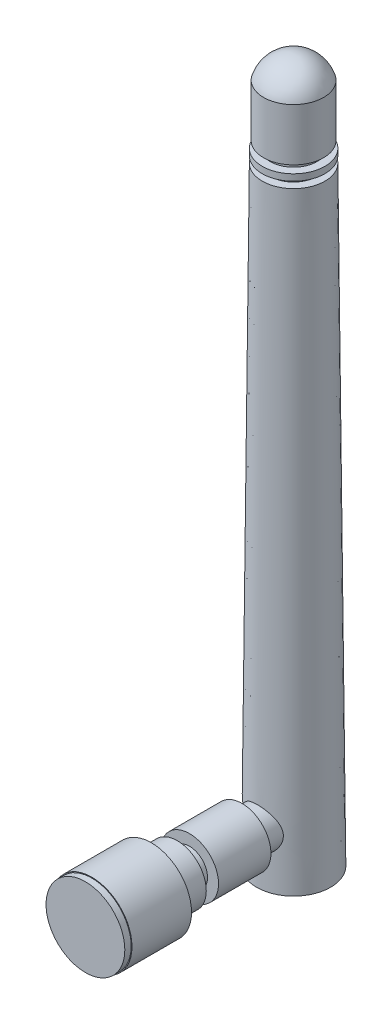
SolidWorks part; units mm, degrees
ref_plane "前视基准面" through (0, 0, 0) normal (0, 0, 1) x (1, 0, 0)
ref_plane "上视基准面" through (0, 0, 0) normal (0, 1, 0) x (1, 0, 0)
ref_plane "右视基准面" through (0, 0, 0) normal (1, 0, 0) x (0, 0, -1)
sketch "草图1" plane through (0, 0, 0) normal (0, 0, 1) x (1, 0, 0)
  line L0 (0, 100.775) -> (0, -11.8825) construction
  line L4 (0, -8.8711) -> (-4.6, -8.8711)
  line L5 (-4.6, -8.8711) -> (-3.9, 66.8787)
  line L6 (-3.9, 66.8787) -> (-2.9, 66.8787)
  line L7 (-2.9, 69.3165) -> (-2.9, 68.4787)
  line L8 (-2.9, 68.4787) -> (-3.9, 68.4787)
  line L9 (-3.9, 68.4787) -> (-3.9, 67.6787)
  line L10 (-3.9, 67.6787) -> (-2.9, 67.6787)
  line L11 (-2.9, 67.6787) -> (-2.9, 66.8787)
  line L12 (-2.9, 69.3165) -> (-3.7351, 69.3165)
  line L13 (-3.7351, 69.3165) -> (-3.7351, 75.8165)
  line L15 (0, 78.6289) -> (0, -8.8711)
  arc A0 (-3.7351, 75.8165) -> (0, 78.6289) centre (0, 74.7424) cw
  dimension "D6" = 3.8865
  dimension "D2" = 87.5
  dimension "D3" = 11.7502
  dimension "D4" = 3.7351
  dimension "D5" = 4.6
  dimension "D7" = 3.9
  dimension "D10" = 0.8
  dimension "D11" = 0.8
  dimension "D12" = 6.5
revolve "旋转1" add sketch "草图1" angle 360 about L0
sketch "草图2" plane through (0, 0, 0) normal (1, 0, 0) x (0, 0, -1)
  line L0 (-44.5035, -2.51) -> (17.4842, -2.51) construction
  line L1 (0, 0) -> (-6.4293, 0)
  line L2 (-6.4293, 0) -> (-6.4293, 1.0994)
  line L3 (-17.7, 1.0994) -> (-14.4735, 1.0994)
  line L4 (-17.7, 1.0994) -> (-17.7, 2.49)
  line L5 (-14.4735, 1.0994) -> (-14.4735, -0.2669)
  line L6 (-17.7, 2.49) -> (-25.1094, 2.49)
  line L7 (-25.1094, 2.49) -> (-25.1094, 2.39)
  line L8 (-25.1094, 2.39) -> (-25.9, 2.39)
  line L9 (-25.9, 2.39) -> (-25.9, -2.51)
  line L10 (-25.9, -2.51) -> (0, -2.51)
  line L11 (0, -2.51) -> (0, 0)
  line L12 (-14.4735, -0.2669) -> (-12.95, -0.2669)
  line L13 (-12.95, -0.2669) -> (-12.95, 1.0994)
  line L14 (-12.95, 1.0994) -> (-6.4293, 1.0994)
  dimension "D1" = 30.5
  dimension "D2" = 4.9
  dimension "D3" = 5
  dimension "D4" = 8.2
revolve "旋转_固定座时" add sketch "草图2" angle 360 about L0
